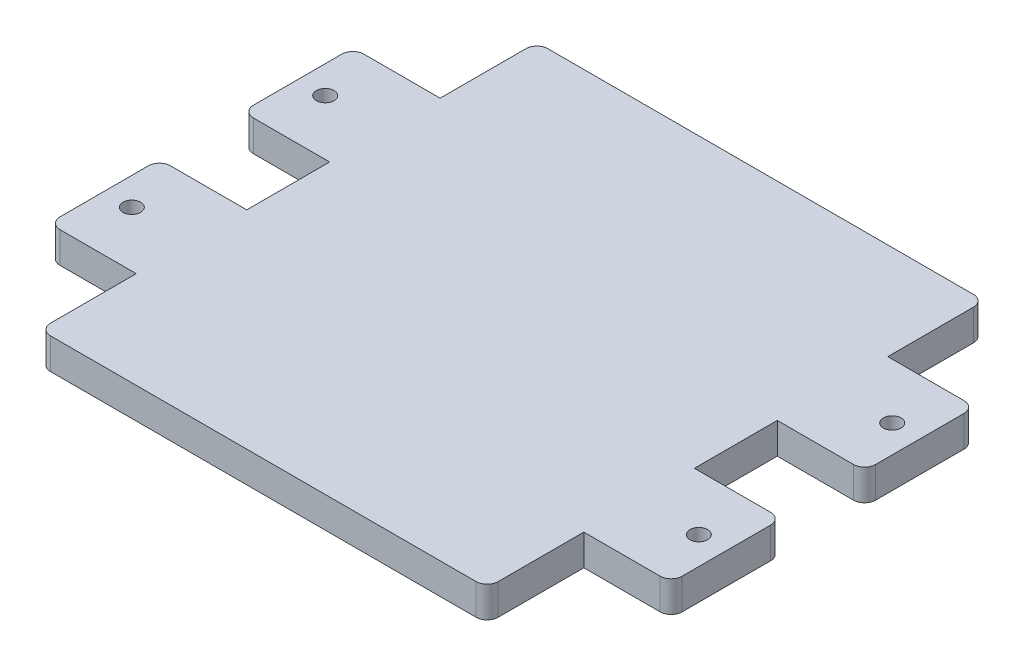
SolidWorks part; units mm, degrees
material "t5ハニカムプラダン"
ref_plane "正面" through (0, 0, 0) normal (0, 0, 1) x (1, 0, 0)
ref_plane "平面" through (0, 0, 0) normal (0, 1, 0) x (1, 0, 0)
ref_plane "右側面" through (0, 0, 0) normal (1, 0, 0) x (0, 0, -1)
sketch "ｽｹｯﾁ1" plane through (0, 0, 0) normal (0, 1, 0) x (1, 0, 0)
  line L1 (-40.5, 45) -> (40.5, 45)
  line L2 (-40.5, 45) -> (-40.5, -45)
  line L3 (-40.5, -45) -> (40.5, -45)
  line L4 (40.5, 45) -> (40.5, -45)
  line L5 (-40.5, 45) -> (40.5, -45) construction
  line L6 (-40.5, -45) -> (40.5, 45) construction
  point P0 (0, 0)
  dimension "D1" = 90
  dimension "D2" = 81
extrude "ﾎﾞｽ - 押し出し1" add sketch "ｽｹｯﾁ1" along normal blind 5.6
sketch "ｽｹｯﾁ2" plane through (0, 5.6, 0) normal (0, 1, 0) x (1, 0, 0)
  line L0 (0, 45) -> (0, 0) construction
  line L1 (40.5, 45) -> (-40.5, 45) construction
  line L2 (0, 0) -> (40.5, 0) construction
  line L3 (40.5, -45) -> (40.5, 45) construction
  line L4 (-56.3, 27.5) -> (-56.3, 7.5)
  line L5 (40.5, 27.5) -> (56.3, 27.5)
  line L6 (40.5, 27.5) -> (40.5, 7.5)
  line L7 (40.5, 7.5) -> (56.3, 7.5)
  line L8 (56.3, 27.5) -> (56.3, 7.5)
  line L9 (-40.5, 7.5) -> (-56.3, 7.5)
  line L10 (-40.5, 27.5) -> (-40.5, 7.5)
  line L11 (-40.5, 27.5) -> (-56.3, 27.5)
  line L12 (-40.5, -27.5) -> (-56.3, -27.5)
  line L13 (-40.5, -27.5) -> (-40.5, -7.5)
  line L14 (-40.5, -7.5) -> (-56.3, -7.5)
  line L15 (56.3, -27.5) -> (56.3, -7.5)
  line L16 (40.5, -7.5) -> (56.3, -7.5)
  line L17 (40.5, -27.5) -> (40.5, -7.5)
  line L18 (40.5, -27.5) -> (56.3, -27.5)
  line L19 (-56.3, -27.5) -> (-56.3, -7.5)
  line L20 (-56.3, 17.5) -> (-51.3, 17.5) construction
  circle A0 centre (-51.3, 17.5) radius 1.6
  circle A1 centre (51.3, 17.5) radius 1.6
  circle A2 centre (51.3, -17.5) radius 1.6
  circle A3 centre (-51.3, -17.5) radius 1.6
  dimension "D4" = 3.2
  dimension "D1" = 15.8
  dimension "D2" = 20
  dimension "D3" = 15
  dimension "D5" = 5
extrude "ﾎﾞｽ - 押し出し2" add sketch "ｽｹｯﾁ2" against normal blind 5.6
fillet "ﾌｨﾚｯﾄ1" radius 2 12 edges at (-40.5, 2.8, -45) (40.5, 2.8, -45) (56.3, 2.8, -27.5) (56.3, 2.8, -7.5) (56.3, 2.8, 7.5) (56.3, 2.8, 27.5) (-56.3, 2.8, -27.5) (-56.3, 2.8, -7.5) (-56.3, 2.8, 27.5) (-56.3, 2.8, 7.5) (40.5, 2.8, 45) (-40.5, 2.8, 45)
